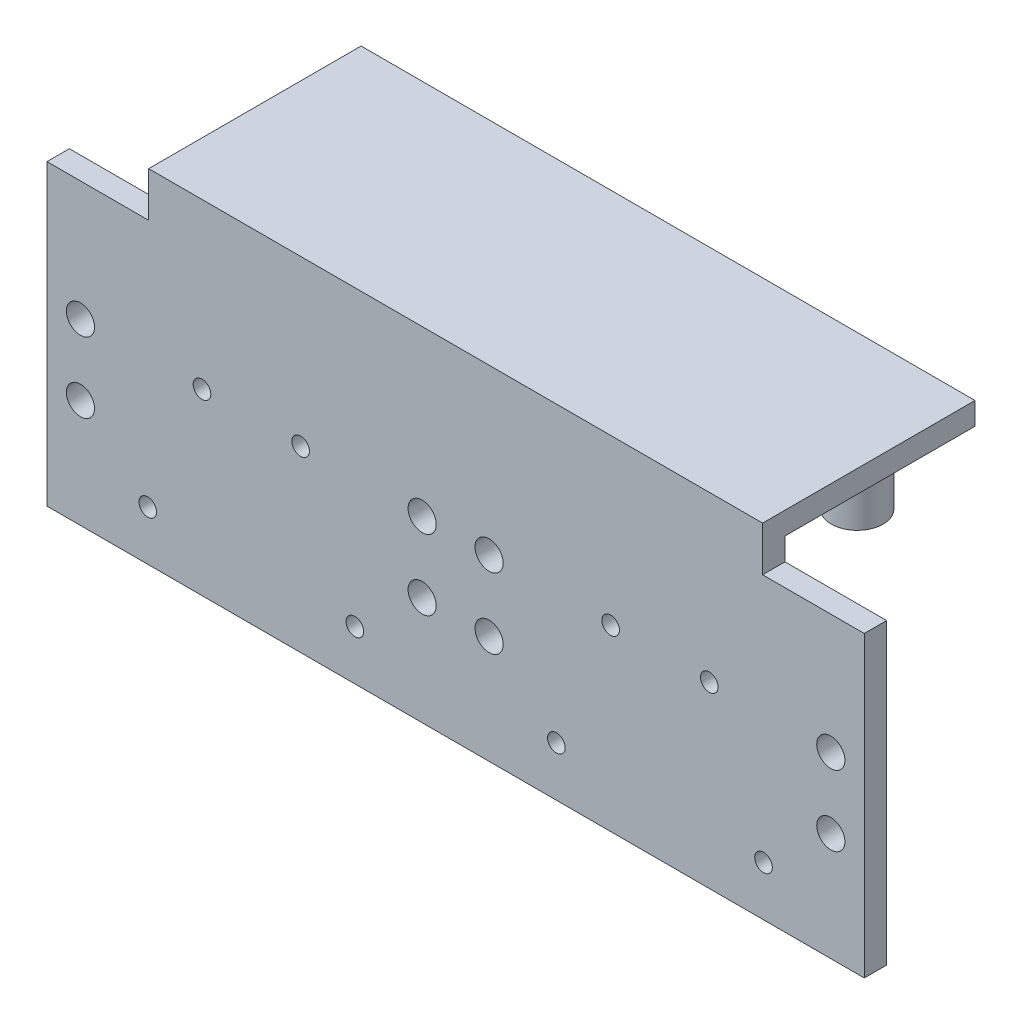
SolidWorks part; units mm, degrees
material "Plain Carbon Steel"
ref_plane "Front" through (0, 0, 0) normal (0, 0, 1) x (1, 0, 0)
ref_plane "Top" through (0, 0, 0) normal (0, 1, 0) x (1, 0, 0)
ref_plane "Right" through (0, 0, 0) normal (1, 0, 0) x (0, 0, -1)
sketch "Sketch1" plane through (0, 0, 0) normal (0, 0, 1) x (1, 0, 0)
  line L0 (29, -37.5) -> (-87, -37.5)
  line L1 (-87, -37.5) -> (-87, -3)
  line L2 (-87, -3) -> (29, -3)
  line L3 (29, -3) -> (29, -37.5)
  line L5 (29, -30) -> (29, -11) construction
  line L6 (-87, -30) -> (-87, -11) construction
  line L8 (-78.5, -3) -> (-37.5, -3) construction
  line L9 (-73, -37.5) -> (-43, -37.5) construction
  dimension "D1" = 0
  dimension "D2" = 0
  dimension "D3" = 0
  dimension "D4" = 0
extrude "Boss-Extrude1" add sketch "Sketch1" along normal blind 3.175
sketch "Sketch2" plane through (0, 0, 0) normal (0, 0, -1) x (-1, 0, 0)
  circle A0 centre (-24.25, -22.13) radius 2
  circle A1 centre (-24.25, -12.13) radius 2
  circle A2 centre (24.25, -12.13) radius 2
  circle A3 centre (24.25, -22.13) radius 2
  circle A4 centre (33.75, -12.13) radius 2
  circle A5 centre (33.75, -22.13) radius 2
  circle A6 centre (82.25, -12.13) radius 2
  circle A7 centre (82.25, -22.13) radius 2
  circle A8 centre (72.6997, -30.4497) radius 1.25
  circle A9 centre (65, -12.13) radius 1.25
  circle A10 centre (51, -12.13) radius 1.25
  circle A11 centre (43.3003, -30.4497) radius 1.25
  circle A12 centre (14.6997, -30.4497) radius 1.25
  circle A13 centre (7, -12.13) radius 1.25
  circle A14 centre (-7, -12.13) radius 1.25
  circle A15 centre (-14.6997, -30.4497) radius 1.25
extrude "Cut-Extrude1" cut sketch "Sketch2" against normal through all
sketch "Sketch3" plane through (0, -3, 0) normal (0, 1, 0) x (1, 0, 0)
  line L8 (29, 0) -> (-87, 0)
  line L9 (-87, 0) -> (-87, -3.175)
  line L10 (-87, -3.175) -> (29, -3.175)
  line L11 (29, -3.175) -> (29, 0)
  line L12 (29, 0) -> (-87, 0)
  line L13 (-87, 0) -> (-87, -3.175)
  line L14 (-87, -3.175) -> (29, -3.175)
  line L15 (29, -3.175) -> (29, 0)
  dimension "D1" = 0
extrude "Boss-Extrude2" add sketch "Sketch3" along normal blind 14.1986 contours L12 L13 L14 L15
sketch "Sketch4" plane through (0, 0, 0) normal (0, 0, -1) x (-1, 0, 0)
  line L0 (87, 11.1986) -> (87, -37.5) construction
  line L1 (-29, 11.1986) -> (87, 11.1986)
  line L2 (-29, 11.1986) -> (-29, 8.0236)
  line L3 (-29, 8.0236) -> (87, 8.0236)
  line L4 (87, 11.1986) -> (87, 8.0236)
  dimension "D1" = 3.175
extrude "Boss-Extrude3" add sketch "Sketch4" along normal blind 26.9748
sketch "Sketch6" plane through (0, 8.0236, 0) normal (0, -1, 0) x (1, 0, 0)
  circle A0 centre (10.05, -14.77) radius 3.6784
  circle A1 centre (-68.05, -14.97) radius 3.6712
extrude "Boss-Extrude4" add sketch "Sketch6" along normal blind 6.35
sketch "Sketch7" plane through (0, 11.1986, 0) normal (0, 1, 0) x (1, 0, 0)
  line L0 (-87, -3.175) -> (29, -3.175) construction
  line L1 (-87, 26.9748) -> (-72.5688, 26.9748)
  line L2 (-87, 26.9748) -> (-87, -3.175)
  line L3 (-87, -3.175) -> (-72.5688, -3.175)
  line L4 (-72.5688, 26.9748) -> (-72.5688, -3.175)
  line L5 (-87, 26.9748) -> (29, 26.9748) construction
  line L6 (29, -3.175) -> (14.5688, -3.175)
  line L7 (29, -3.175) -> (29, 26.9748)
  line L8 (29, 26.9748) -> (14.5688, 26.9748)
  line L9 (14.5688, -3.175) -> (14.5688, 26.9748)
extrude "Cut-Extrude2" cut sketch "Sketch7" against normal blind 6.35
